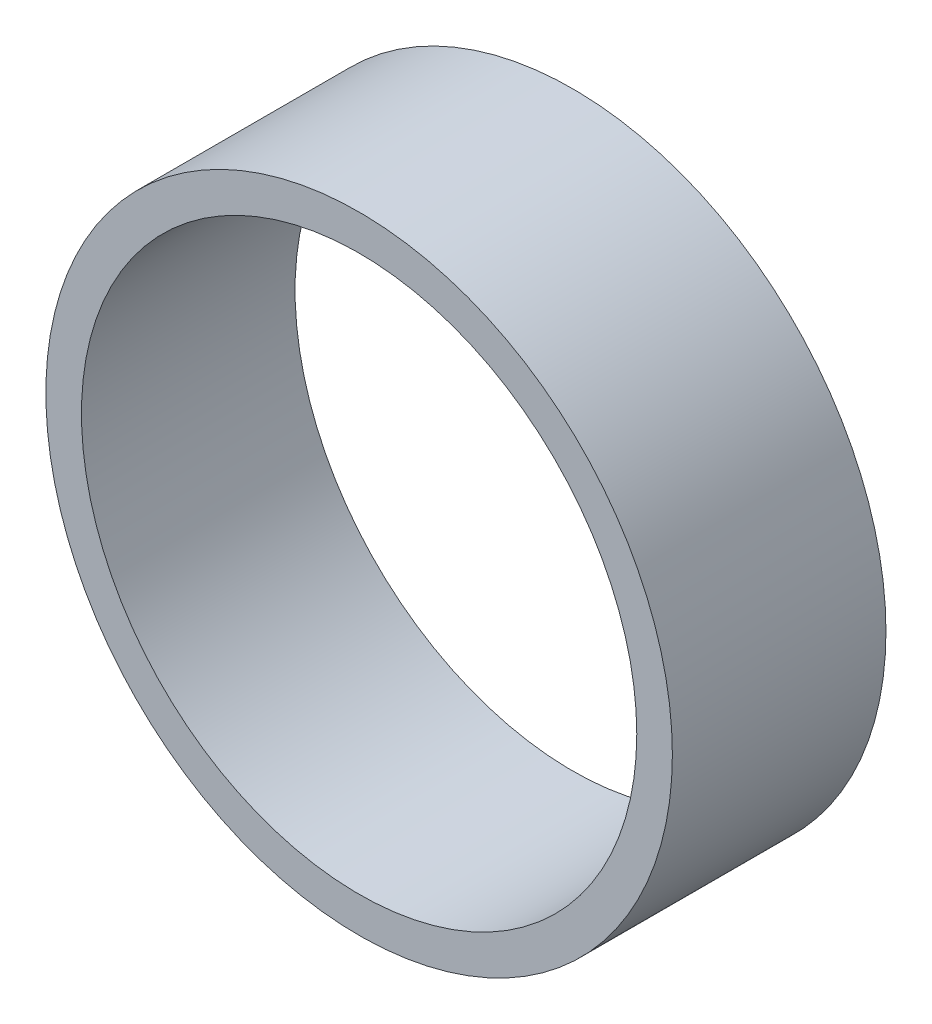
SolidWorks part; units mm, degrees
ref_plane "Plan de face" through (0, 0, 0) normal (0, 0, 1) x (1, 0, 0)
ref_plane "Plan de dessus" through (0, 0, 0) normal (0, 1, 0) x (1, 0, 0)
ref_plane "Plan de droite" through (0, 0, 0) normal (1, 0, 0) x (0, 0, -1)
sketch "Esquisse1" plane through (0, 0, 0) normal (0, 0, 1) x (1, 0, 0)
  circle A0 centre (0, 0) radius 39
  circle A1 centre (0, 0) radius 44
  dimension "D1" = 5
  dimension "D2" = 78
extrude "Boss.-Extru.1" add sketch "Esquisse1" along normal blind 30
move or copy body "Body-Move/Copy1" [suppressed] bodies to move or copy 101
